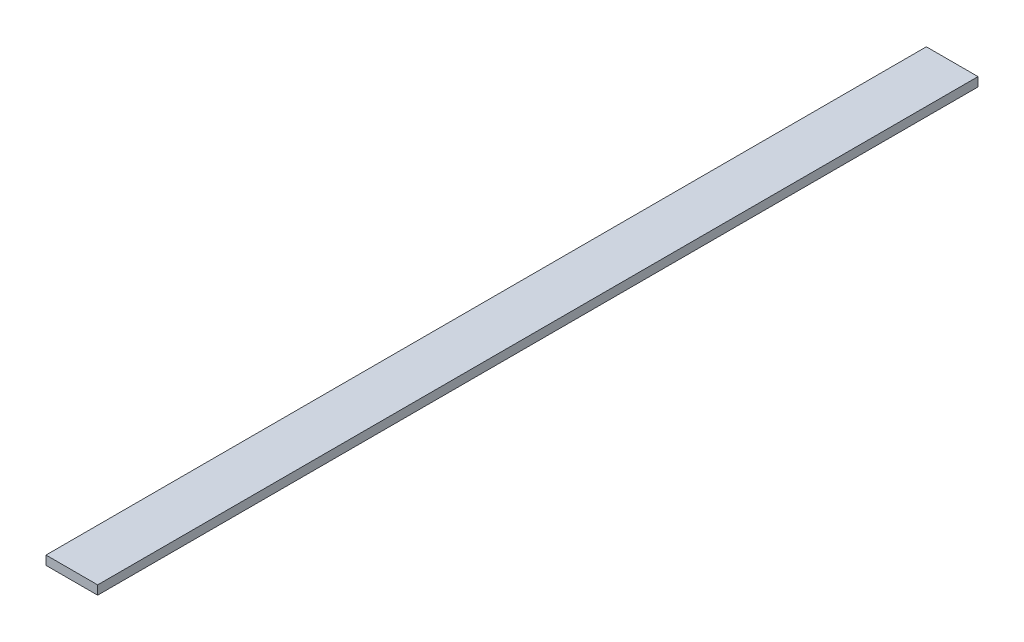
SolidWorks part; units mm, degrees
ref_plane "Front Plane" through (0, 0, 0) normal (0, 0, 1) x (1, 0, 0)
ref_plane "Top Plane" through (0, 0, 0) normal (0, 1, 0) x (1, 0, 0)
ref_plane "Right Plane" through (0, 0, 0) normal (1, 0, 0) x (0, 0, -1)
sketch "Sketch1" plane through (0, 0, 0) normal (0, 0, 1) x (1, 0, 0)
  line L1 (-57.5, 10) -> (57.5, 10)
  line L2 (-57.5, 10) -> (-57.5, -10)
  line L3 (-57.5, -10) -> (57.5, -10)
  line L4 (57.5, 10) -> (57.5, -10)
  line L5 (-57.5, 10) -> (57.5, -10) construction
  line L6 (-57.5, -10) -> (57.5, 10) construction
  point P0 (0, 0)
extrude "Boss-Extrude1" add sketch "Sketch1" along normal blind 1960 contours L1 L4 L3 L2
